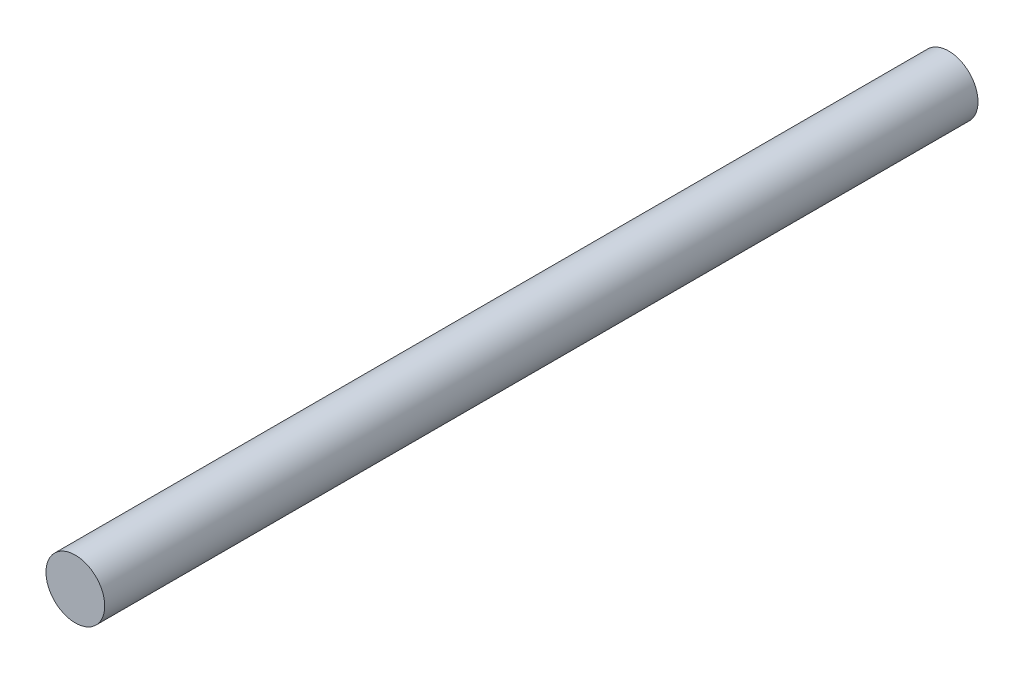
SolidWorks part; units mm, degrees
ref_plane "Front Plane" through (0, 0, 0) normal (0, 0, 1) x (1, 0, 0)
ref_plane "Top Plane" through (0, 0, 0) normal (0, 1, 0) x (1, 0, 0)
ref_plane "Right Plane" through (0, 0, 0) normal (1, 0, 0) x (0, 0, -1)
sketch "Sketch1" plane through (0, 0, 0) normal (0, 0, 1) x (1, 0, 0)
  circle A0 centre (0, 0) radius 5
  dimension "D1" = 10
extrude "Boss-Extrude1" add sketch "Sketch1" along normal mid plane 148.5
